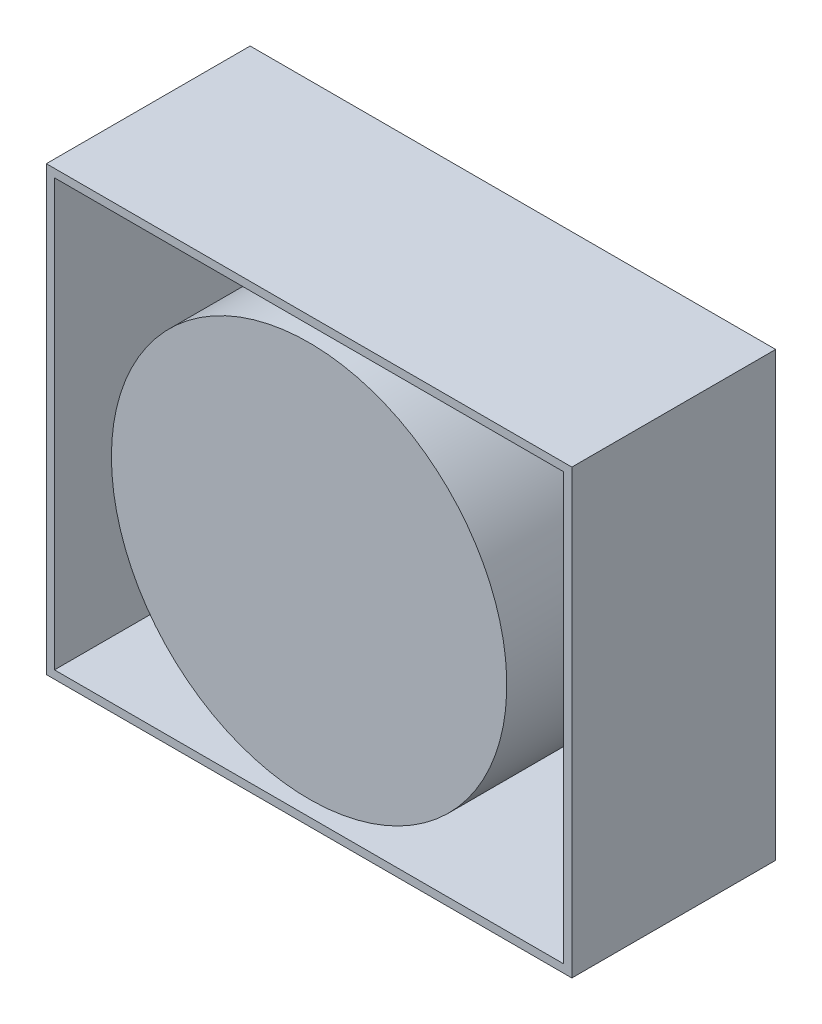
SolidWorks part; units mm, degrees
ref_plane "Front Plane" through (0, 0, 0) normal (0, 0, 1) x (1, 0, 0)
ref_plane "Top Plane" through (0, 0, 0) normal (0, 1, 0) x (1, 0, 0)
ref_plane "Right Plane" through (0, 0, 0) normal (1, 0, 0) x (0, 0, -1)
sketch "Sketch1" plane through (0, 0, 0) normal (0, 0, 1) x (1, 0, 0)
  line L0 (-64.4613, 54.2738) -> (-64.4613, -54.2738)
  line L1 (-62.4613, 52.2738) -> (62.4613, 52.2738)
  line L2 (-62.4613, 52.2738) -> (-62.4613, -52.2738)
  line L3 (-62.4613, -52.2738) -> (62.4613, -52.2738)
  line L4 (62.4613, 52.2738) -> (62.4613, -52.2738)
  line L5 (-62.4613, 52.2738) -> (62.4613, -52.2738) construction
  line L6 (-62.4613, -52.2738) -> (62.4613, 52.2738) construction
  line L7 (-64.4613, -54.2738) -> (64.4613, -54.2738)
  line L8 (64.4613, 54.2738) -> (64.4613, -54.2738)
  line L9 (-64.4613, 54.2738) -> (64.4613, 54.2738)
  point P0 (0, 0)
  dimension "D1" = 2
extrude "Boss-Extrude1" add sketch "Sketch1" along normal blind 50
sketch "Sketch2" plane through (0, 0, 0) normal (0, 0, 1) x (1, 0, 0)
  circle A0 centre (0, 0) radius 48.4966
extrude "Boss-Extrude2" add sketch "Sketch2" along normal up to surface (50 mm away) separate body up to face at (0, 0, 50)
sketch "Sketch3" plane through (0, 0, 0) normal (0, 0, 1) x (1, 0, 0)
  circle A0 centre (-51.1264, 41.5168) radius 6.9941
  circle A1 centre (46.4615, 43.756) radius 6.1207
extrude "Boss-Extrude3" add sketch "Sketch3" along normal blind 20 separate body
